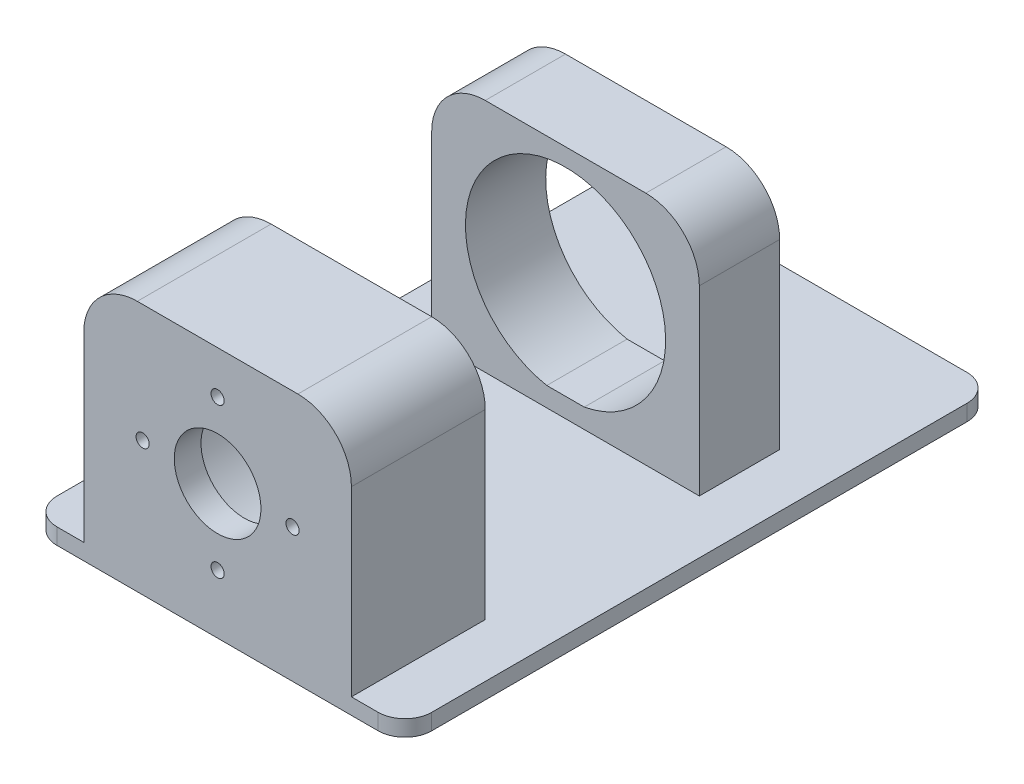
SolidWorks part; units mm, degrees
ref_plane "Front Plane" through (0, 0, 0) normal (0, 0, 1) x (1, 0, 0)
ref_plane "Top Plane" through (0, 0, 0) normal (0, 1, 0) x (1, 0, 0)
ref_plane "Right Plane" through (0, 0, 0) normal (1, 0, 0) x (0, 0, -1)
sketch "Sketch1" plane through (0, 0, 45.685) normal (0, 0, 1) x (1, 0, 0)
  line L0 (-25.1743, 8.9776) -> (2.8257, 8.9776) construction
  line L1 (-11.1743, 22.9776) -> (-11.1743, -5.0224) construction
  line L3 (-36.1743, 30.9776) -> (13.8257, 30.9776)
  line L4 (-36.1743, 30.9776) -> (-36.1743, -13.0224)
  line L5 (-36.1743, -13.0224) -> (13.8257, -13.0224)
  line L6 (13.8257, 30.9776) -> (13.8257, -13.0224)
  line L7 (-36.1743, 30.9776) -> (13.8257, -13.0224) construction
  line L8 (-36.1743, -13.0224) -> (13.8257, 30.9776) construction
  circle A0 centre (-11.1743, 22.9776) radius 1.2295 construction
  circle A1 centre (2.8257, 8.9776) radius 1.2295 construction
  circle A2 centre (-11.1743, -5.0224) radius 1.2295 construction
  circle A3 centre (-25.1743, 8.9776) radius 1.2295 construction
  circle A4 centre (-11.1743, 22.9776) radius 1.2295
  circle A5 centre (2.8257, 8.9776) radius 1.2295
  circle A6 centre (-11.1743, -5.0224) radius 1.2295
  circle A7 centre (-25.1743, 8.9776) radius 1.2295
  circle A9 centre (-11.1743, 8.9776) radius 8.1 construction
  circle A10 centre (-11.1743, 8.9776) radius 8.1
  point P12 (-11.1743, 8.9776)
  dimension "D1" = 50
  dimension "D2" = 44
extrude "Boss-Extrude1" add sketch "Sketch1" along normal blind 5
sketch "Sketch2" plane through (0, 0, 45.685) normal (0, 0, -1) x (-1, 0, 0)
  line L0 (-13.8257, 30.9776) -> (36.1743, 30.9776)
  line L1 (-13.8257, -13.0224) -> (-13.8257, 30.9776) construction
  line L2 (36.1743, 30.9776) -> (36.1743, -13.0224) construction
  line L3 (36.1743, 30.9776) -> (36.1743, -13.0224)
  line L4 (36.1743, -13.0224) -> (-13.8257, -13.0224)
  line L5 (-13.8257, -13.0224) -> (-13.8257, 30.9776)
  line L6 (-13.8257, 30.9776) -> (36.1743, 30.9776) construction
  circle A0 centre (11.1743, 8.9776) radius 18 construction
  circle A1 centre (11.1743, 8.9776) radius 18
  dimension "D1" = 0
extrude "Boss-Extrude2" add sketch "Sketch2" along normal blind 20
sketch "Sketch4" plane through (0, -13.0224, 0) normal (0, -1, 0) x (1, 0, 0)
  line L0 (-36.1743, 50.685) -> (13.8257, 50.685) construction
  line L1 (23.8257, -59.315) -> (-46.1743, -59.315)
  line L2 (23.8257, -59.315) -> (23.8257, 50.685)
  line L3 (23.8257, 50.685) -> (-46.1743, 50.685)
  line L4 (-46.1743, -59.315) -> (-46.1743, 50.685)
  line L5 (-36.1743, 50.685) -> (-36.1743, 25.685) construction
  dimension "D1" = 70
  dimension "D2" = 110
  dimension "D3" = 0
  dimension "D4" = 10
extrude "Boss-Extrude3" add sketch "Sketch4" along normal blind 3
ref_plane "Plane1" through (0, 0, -14.315) normal (0, 0, -1) x (-1, 0, 0)
sketch "Sketch6" plane through (0, 0, -14.315) normal (0, 0, -1) x (-1, 0, 0)
  line L0 (7.6743, -9.3919) -> (14.6743, -9.3919)
  line L1 (-13.8257, -13.0224) -> (36.1743, -13.0224) construction
  line L2 (36.1743, -13.0224) -> (36.1743, 30.9776) construction
  line L3 (36.1743, 30.9776) -> (-13.8257, 30.9776) construction
  line L4 (-13.8257, 30.9776) -> (-13.8257, -13.0224) construction
  line L5 (-13.8257, -13.0224) -> (36.1743, -13.0224)
  line L6 (36.1743, -13.0224) -> (36.1743, 30.9776)
  line L7 (36.1743, 30.9776) -> (-13.8257, 30.9776)
  line L8 (-13.8257, 30.9776) -> (-13.8257, -13.0224)
  arc A0 (14.6743, -9.3919) -> (7.6743, -9.3919) centre (11.1743, 8.9776) ccw construction
  arc A1 (14.6743, -9.3919) -> (7.6743, -9.3919) centre (11.1743, 8.9776) ccw
extrude "Boss-Extrude4" add sketch "Sketch6" along normal blind 15
fillet "Fillet1" radius 10 4 edges at (13.8257, 30.9776, -21.815) (13.8257, 30.9776, 38.185) (-36.1743, 30.9776, 38.185) (-36.1743, 30.9776, -21.815)
fillet "Fillet3" radius 5 4 edges at (-46.1743, -14.5224, -59.315) (23.8257, -14.5224, -59.315) (23.8257, -14.5224, 50.685) (-46.1743, -14.5224, 50.685)
